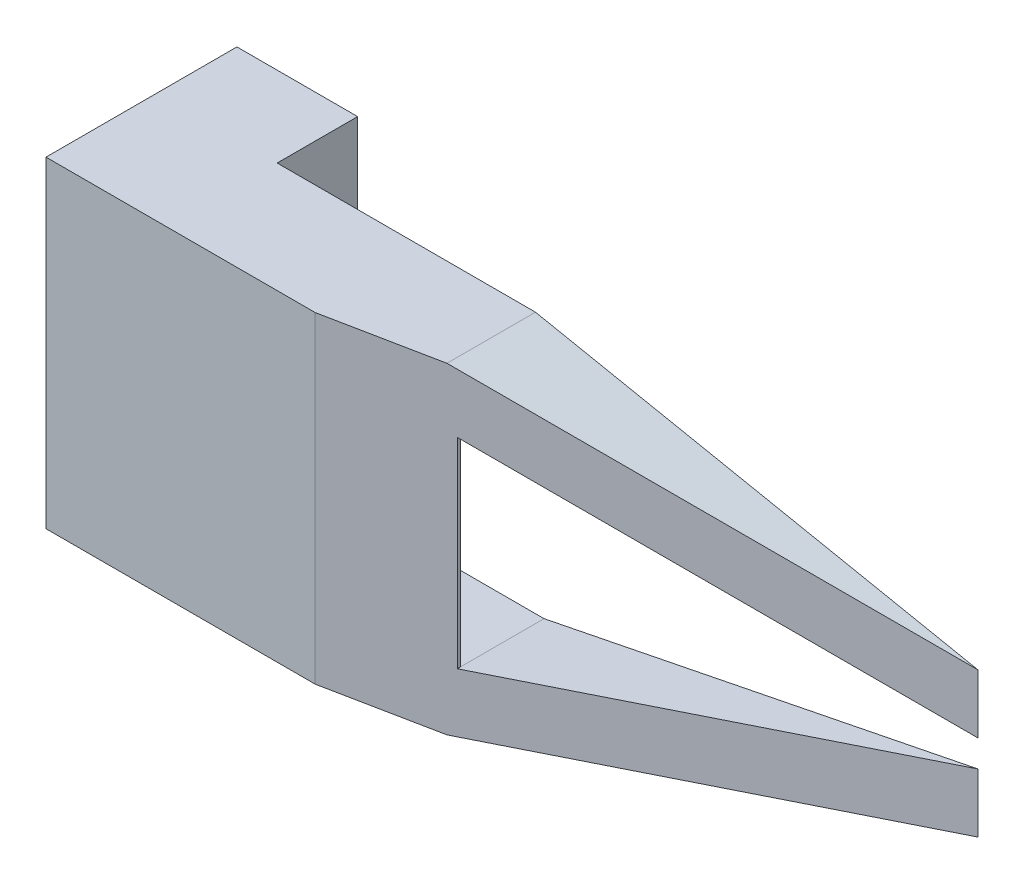
SolidWorks part; units mm, degrees
ref_plane "Front Plane" through (0, 0, 0) normal (0, 0, 1) x (1, 0, 0)
ref_plane "Top Plane" through (0, 0, 0) normal (0, 1, 0) x (1, 0, 0)
ref_plane "Right Plane" through (0, 0, 0) normal (1, 0, 0) x (0, 0, -1)
sketch "Sketch1" plane through (0, 0, 0) normal (0, 1, 0) x (1, 0, 0)
  line L0 (20.7864, 2.1573) -> (8.7864, 2.1573)
  line L1 (20.7864, 2.1573) -> (39.4174, 5.8835)
  line L2 (8.7864, 5.8835) -> (39.4174, 5.8835)
  line L3 (8.7864, 2.1573) -> (8.7864, 5.8835)
extrude "Boss-Extrude1" add sketch "Sketch1" along normal blind 12
sketch "Sketch4" plane through (0, 0, -5.8835) normal (0, 0, -1) x (-1, 0, 0)
  line L0 (-39.4174, 3.3) -> (-22.9174, 0)
  line L2 (-39.4174, 0) -> (-39.4174, 3.3)
  line L3 (-39.4174, 0) -> (-22.9174, 0)
extrude "Cut-Extrude1" cut sketch "Sketch4" against normal blind 8
sketch "Sketch5" plane through (0, 0, -5.8835) normal (0, 0, -1) x (-1, 0, 0)
  line L0 (-39.4174, 6.5) -> (-23.2378, 9.7359)
  line L2 (-39.4174, 5.5) -> (-23.2378, 2.2641)
  line L3 (-23.2378, 2.2641) -> (-23.2378, 9.7359)
  line L5 (-39.4174, 5.5) -> (-39.4174, 6.5)
extrude "Cut-Extrude2" cut sketch "Sketch5" against normal blind 8
ref_plane "Plane1" through (0, 6, 0) normal (0, 1, 0) x (1, 0, 0)
mirror "Mirror1" about plane through (0, 6, 0) normal (0, 1, 0) of "Cut-Extrude1"
sketch "Sketch6" plane through (0, 0, -5.8835) normal (0, 0, -1) x (-1, 0, 0)
  line L1 (-8.7864, 12) -> (-13.2864, 12)
  line L2 (-8.7864, 12) -> (-8.7864, 0)
  line L3 (-13.2864, 0) -> (-8.7864, 0)
  line L4 (-13.2864, 12) -> (-13.2864, 0)
extrude "Boss-Extrude2" add sketch "Sketch6" along normal blind 3
sketch "Sketch7" plane through (0, 12, 0) normal (0, 1, 0) x (1, 0, 0)
  line L0 (20.7864, 2.1573) -> (18.8252, 1.765)
  line L1 (18.8252, 1.765) -> (8.7864, 1.765)
  line L2 (8.7864, 1.765) -> (8.7864, 2.1573)
  line L3 (8.7864, 2.1573) -> (20.7864, 2.1573)
extrude "Boss-Extrude3" add sketch "Sketch7" against normal blind 12
sketch "Sketch8" plane through (8.7864, 0, 0) normal (-1, 0, 0) x (0, 0, 1)
  line L0 (-2.765, 2.2641) -> (-2.765, 9.7359)
  line L2 (-2.6476, 9.7359) -> (-5.8835, 9.7359) construction
  line L3 (-2.765, 9.7359) -> (-6.4435, 9.7359)
  line L4 (-2.765, 2.2641) -> (-6.4435, 2.2641)
  line L5 (-1.765, 0) -> (-1.765, 12) construction
  line L6 (-6.4435, 9.7359) -> (-6.4435, 2.2641)
  dimension "D1" = 1
extrude "Cut-Extrude3" cut sketch "Sketch8" against normal up to vertex
